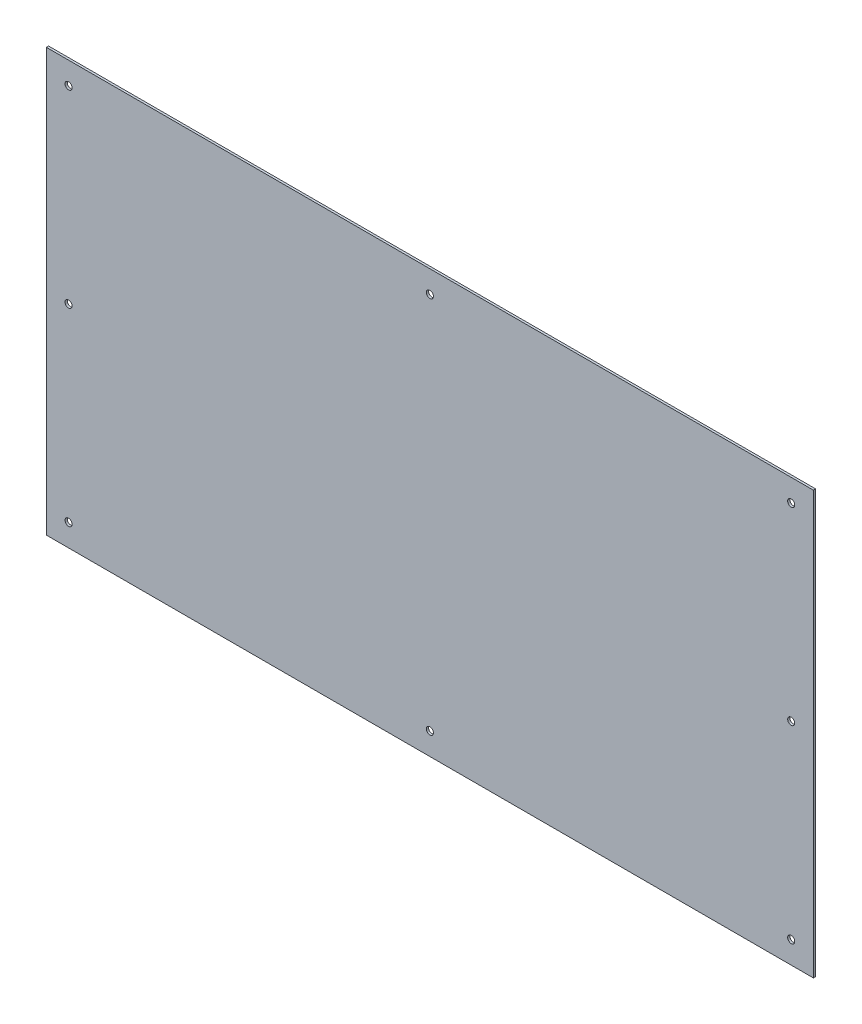
SolidWorks part; units mm, degrees
ref_plane "Alzado" through (0, 0, 0) normal (0, 0, 1) x (1, 0, 0)
ref_plane "Planta" through (0, 0, 0) normal (0, 1, 0) x (1, 0, 0)
ref_plane "Vista lateral" through (0, 0, 0) normal (1, 0, 0) x (0, 0, -1)
sketch "Croquis1" plane through (0, 0, 0) normal (0, 0, 1) x (1, 0, 0)
  line L0 (-67, -210) -> (-67, 216) construction
  line L1 (-67, 3) -> (-42.9748, 3) construction
  line L2 (-412, -187) -> (278, -187)
  line L3 (-412, -187) -> (-412, 193)
  line L4 (-412, 193) -> (278, 193)
  line L5 (278, -187) -> (278, 193)
  line L6 (-412, -187) -> (278, 193) construction
  line L7 (-412, 193) -> (278, -187) construction
  dimension "D1" = 690
  dimension "D2" = 380
extrude "Saliente-Extruir1" add sketch "Croquis1" along normal blind 2
sketch "Croquis2" plane through (0, 0, 2) normal (0, 0, 1) x (1, 0, 0)
  line L0 (-412, 3) -> (278, 3) construction
  line L1 (-412, 193) -> (-412, -187) construction
  line L2 (278, -187) -> (278, 193) construction
  line L3 (278, 3) -> (-67, 3) construction
  line L4 (-67, 3) -> (-67, 193) construction
  line L5 (278, 193) -> (-412, 193) construction
  line L7 (-392, 173) -> (258, 173) construction
  line L8 (-392, 173) -> (-392, -167) construction
  line L9 (-392, -167) -> (258, -167) construction
  line L10 (258, 173) -> (258, -167) construction
  line L11 (-392, 173) -> (258, -167) construction
  line L12 (-392, -167) -> (258, 173) construction
  circle A0 centre (-392, 173) radius 3.175
  circle A1 centre (258, 173) radius 3.175
  circle A2 centre (258, -167) radius 3.175
  circle A3 centre (-392, -167) radius 3.175
  circle A4 centre (-392, 3) radius 3.175
  circle A5 centre (258, 3) radius 3.175
  circle A6 centre (-67, 173) radius 3.175
  circle A7 centre (-67, -167) radius 3.175
  dimension "D3" = 6.35
  dimension "D4" = 6.35
  dimension "D5" = 6.35
  dimension "D1" = 20
  dimension "D2" = 20
extrude "Cortar-Extruir2" cut sketch "Croquis2" against normal blind 10
